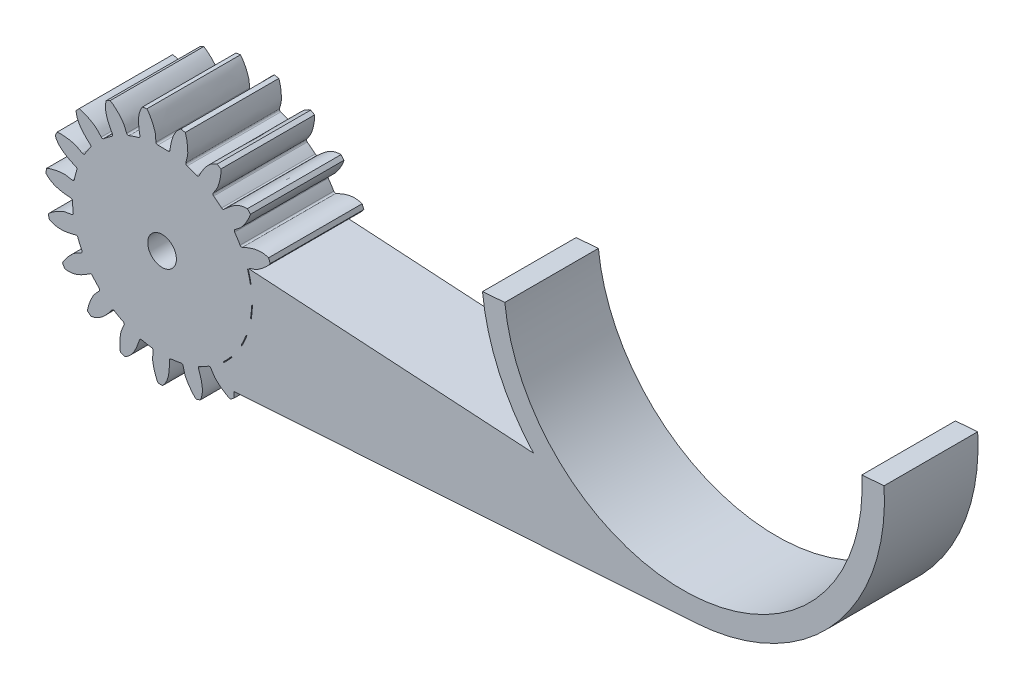
SolidWorks part; units mm, degrees
ref_plane "前视基准面" through (0, 0, 0) normal (0, 0, 1) x (1, 0, 0)
ref_plane "上视基准面" through (0, 0, 0) normal (0, 1, 0) x (1, 0, 0)
ref_plane "右视基准面" through (0, 0, 0) normal (1, 0, 0) x (0, 0, -1)
other "Configuration Table"
sketch "草图3" plane through (0, 0, 0) normal (0, 0, 1) x (1, 0, 0)
  circle A0 centre (0, 0) radius 13
  circle A1 centre (0, 0) radius 10
  dimension "D1" = 26
  dimension "D2" = 20
extrude "凸台-拉伸1" add sketch "草图3" along normal blind 4 contours A1 | A0 A1
sketch "草图6" plane through (0, 0, 4) normal (0, 0, 1) x (1, 0, 0)
  line L0 (0, 14.519) -> (0, -0.3622) construction
  line L5 (0, 0) -> (-1.6968, 12.8888) construction
  line L6 (-1.6968, 12.8888) -> (-1.8736, 14.2316)
  line L7 (-1.8736, 14.2316) -> (3.0009, 14.404)
  line L8 (3.0009, 14.404) -> (2.085, 12.8317)
  arc A0 (0.6559, 9.9785) -> (-0.4764, 9.9886) centre (0, 0) ccw
  circle A1 centre (0, 0) radius 13 construction
  arc A2 (0.6559, 9.9785) -> (0.8668, 10.1484) centre (0.669, 10.178) ccw
  arc A3 (-0.6854, 10.1744) -> (-0.4764, 9.9886) centre (-0.4859, 10.1884) ccw
  spline S0 degree 3 poles (-1.6968, 12.8888) (-1.3404, 12.4914) (-0.7219, 11.2236) (-0.7215, 10.6885) (-0.6854, 10.1744) knots 0 0 0 0 0.644244 0.940775 0.940775 0.940775 0.940775
  spline S1 degree 3 poles (2.085, 12.8317) (1.4718, 12.3854) (1.0735, 11.4242) (0.9081, 10.424) (0.8668, 10.1484) knots 0 0 0 0 0.67612 0.940775 0.940775 0.940775 0.940775
  dimension "D1" = 20
  dimension "D2" = 0.2
  dimension "D3" = 7.5
extrude "切除-拉伸2" cut sketch "草图6" against normal through all both
pattern_circular "阵列(圆周)4" count 19 every 18.947 about axis through (0, 0, 4) along (0, 0, 1) of "切除-拉伸2"
sketch "草图7" plane through (0, 0, 4) normal (0, 0, 1) x (1, 0, 0)
  circle A0 centre (0, 0) radius 12.5
  dimension "D1" = 25
ref_plane "基准面3" through (0, 0, 2) normal (0, 0, 1) x (1, 0, 0)
sketch "草图8" plane through (0, 0, 0) normal (0, 0, -1) x (-1, 0, 0)
  circle A5 centre (0, 0) radius 4.05
  dimension "D1" = 8.1
extrude "切除-拉伸4" cut sketch "草图8" against normal through all both
sketch "草图9" plane through (0, 0, 4) normal (0, 0, 1) x (1, 0, 0)
  line L8 (-1.8658, 22.9242) -> (0, 0) construction
  line L9 (41.4695, 1.1745) -> (9.5915, 3.1189)
  line L13 (0.8182, -10.0526) -> (59.6313, -6.1804)
  line L15 (-0.9329, 11.4621) -> (100.4696, 19.7151) construction
  line L16 (100.1482, 19.1873) -> (20.1614, 12.6773) construction
  line L17 (80.614, 17.5974) -> (78.1215, 17.3946)
  line L18 (0, 0) -> (20.4337, 1.6631) construction
  line L23 (0, 0) -> (1.9441, -23.887) construction
  line L26 (38.2658, 14.1508) -> (35.7734, 13.9479)
  arc A20 (0.8182, -10.0526) -> (9.5915, 3.1189) centre (0, 0) ccw
  arc A21 (38.2658, 14.1508) -> (78.1215, 17.3946) centre (58.1531, 16.271) ccw
  arc A22 (59.6313, -6.1804) -> (80.614, 17.5974) centre (58.1531, 16.271) ccw
  arc A23 (35.7734, 13.9479) -> (41.4695, 1.1745) centre (58.1531, 16.271) ccw
  dimension "D1" = 40
  dimension "D3" = 45
  dimension "D2" = 0.5
sketch "草图10" plane through (0, 0, 0) normal (0, 0, -1) x (-1, 0, 0)
  circle A0 centre (0, 0) radius 4.5
  dimension "D1" = 9
extrude "切除-拉伸5" cut sketch "草图10" against normal blind 0.6
sketch "草图11" plane through (0, 0, 4) normal (0, 0, 1) x (1, 0, 0)
  circle A0 centre (0, 0) radius 4.5
  dimension "D1" = 9
extrude "切除-拉伸6" cut sketch "草图11" against normal blind 0.6
sketch "草图15" plane through (0, 0, 4) normal (0, 0, 1) x (1, 0, 0)
  arc A62 (10.6318, -7.4809) -> (10.9134, -7.0638) centre (0, 0) ccw
  arc A64 (9.6948, 3.1621) -> (9.566, 2.9139) centre (9.7574, 2.9722) ccw
  arc A65 (12.0778, 4.8089) -> (11.8827, 5.2728) centre (0, 0) ccw
  arc A66 (8.7124, 4.9086) -> (8.97, 4.825) centre (8.8866, 5.0068) ccw
  arc A67 (8.7124, 4.9086) -> (8.1016, 5.8621) centre (0, 0) ccw
  arc A68 (8.1428, 6.1387) -> (8.1016, 5.8621) centre (8.2636, 5.9793) ccw
  arc A69 (9.862, 8.47) -> (9.5268, 8.8454) centre (0, 0) ccw
  arc A70 (6.6465, 7.4716) -> (6.9173, 7.4761) centre (6.7794, 7.621) ccw
  arc A71 (6.6465, 7.4716) -> (5.7592, 8.1751) centre (0, 0) ccw
  arc A72 (5.7084, 8.4501) -> (5.7592, 8.1751) centre (5.8744, 8.3386) ccw
  arc A73 (6.5774, 11.2133) -> (6.1385, 11.4595) centre (0, 0) ccw
  arc A74 (3.8603, 9.2248) -> (4.115, 9.3171) centre (3.9375, 9.4093) ccw
  arc A75 (3.8603, 9.2248) -> (2.7927, 9.6021) centre (0, 0) ccw
  arc A76 (2.6553, 9.8457) -> (2.7927, 9.6021) centre (2.8486, 9.7942) ccw
  arc A77 (2.5801, 12.7414) -> (2.085, 12.8317) centre (0, 0) ccw
  arc A78 (0.6559, 9.9785) -> (0.8668, 10.1484) centre (0.669, 10.178) ccw
  arc A79 (0.6559, 9.9785) -> (-0.4764, 9.9886) centre (0, 0) ccw
  arc A80 (-0.6854, 10.1744) -> (-0.4764, 9.9886) centre (-0.4859, 10.1884) ccw
  arc A81 (-1.6968, 12.8888) -> (-2.1944, 12.8134) centre (0, 0) ccw
  arc A82 (-2.6197, 9.6508) -> (-2.4754, 9.88) centre (-2.6721, 9.8438) ccw
  arc A83 (-2.6197, 9.6508) -> (-3.6939, 9.2927) centre (0, 0) ccw
  arc A84 (-3.9519, 9.4006) -> (-3.6939, 9.2927) centre (-3.7678, 9.4786) ccw
  arc A85 (-5.7899, 11.6395) -> (-6.236, 11.4067) centre (0, 0) ccw
  arc A86 (-5.6113, 8.2773) -> (-5.5493, 8.5409) centre (-5.7236, 8.4428) ccw
  arc A87 (-5.6113, 8.2773) -> (-6.5111, 7.5898) centre (0, 0) ccw
  arc A88 (-6.7902, 7.608) -> (-6.5111, 7.5898) centre (-6.6413, 7.7416) ccw
  arc A89 (-9.2555, 9.1288) -> (-9.6019, 8.7638) centre (0, 0) ccw
  arc A90 (-7.9949, 6.0068) -> (-8.0218, 6.2763) centre (-8.1548, 6.1269) ccw
  arc A91 (-7.9949, 6.0068) -> (-8.6227, 5.0644) centre (0, 0) ccw
  arc A92 (-8.8926, 4.9911) -> (-8.6227, 5.0644) centre (-8.7952, 5.1657) ccw
  arc A93 (-11.7181, 5.629) -> (-11.9272, 5.1712) centre (0, 0) ccw
  arc A94 (-9.5121, 3.0854) -> (-9.6251, 3.3315) centre (-9.7024, 3.1471) ccw
  arc A95 (-9.5121, 3.0854) -> (-9.7999, 1.9902) centre (0, 0) ccw
  arc A96 (-10.0314, 1.8332) -> (-9.7999, 1.9902) centre (-9.9959, 2.03) ccw
  arc A97 (-12.9109, 1.5191) -> (-12.9601, 1.0182) centre (0, 0) ccw
  arc A98 (-9.9985, -0.1704) -> (-10.1853, 0.0258) centre (-10.1985, -0.1738) ccw
  arc A99 (-9.9985, -0.1704) -> (-9.9152, -1.2996) centre (0, 0) ccw
  arc A100 (-10.0831, -1.5233) -> (-9.9152, -1.2996) centre (-10.1135, -1.3256) ccw
  arc A101 (-12.7046, -2.7554) -> (-12.5885, -3.2451) centre (0, 0) ccw
  arc A102 (-9.4015, -3.4077) -> (-9.6418, -3.2828) centre (-9.5895, -3.4758) ccw
  arc A103 (-9.4015, -3.4077) -> (-8.956, -4.4487) centre (0, 0) ccw
  arc A104 (-9.0421, -4.7147) -> (-8.956, -4.4487) centre (-9.1351, -4.5376) ccw
  arc A105 (-11.1216, -6.7313) -> (-10.8527, -7.1567) centre (0, 0) ccw
  arc A106 (-7.7856, -6.2757) -> (-8.0535, -6.2356) centre (-7.9413, -6.4012) ccw
  arc A107 (-7.7856, -6.2757) -> (-7.0262, -7.1156) centre (0, 0) ccw
  arc A108 (-7.0213, -7.3953) -> (-7.0262, -7.1156) centre (-7.1667, -7.2579) ccw
  arc A109 (-8.3333, -9.9777) -> (-7.9409, -10.2928) centre (0, 0) ccw
  arc A110 (-5.326, -8.4636) -> (-5.5924, -8.5127) centre (-5.4326, -8.6329) ccw
  arc A111 (-5.326, -8.4636) -> (-4.3351, -9.0115) centre (0, 0) ccw
  arc A112 (-4.2397, -9.2744) -> (-4.3351, -9.0115) centre (-4.4218, -9.1917) ccw
  arc A113 (-4.6421, -12.143) -> (-4.1686, -12.3135) centre (0, 0) ccw
  arc A114 (-2.2893, -9.7344) -> (-2.5253, -9.8673) centre (-2.3351, -9.9291) ccw
  arc A115 (-2.2893, -9.7344) -> (-1.1742, -9.9308) centre (0, 0) ccw
  arc A116 (-0.9986, -10.1485) -> (-1.1742, -9.9308) centre (-1.1976, -10.1294) ccw
  arc A117 (-0.4477, -12.9923) -> (0.0555, -12.9999) centre (0, 0) ccw
  arc A118 (0.9955, -9.9503) -> (0.8154, -10.1526) centre (1.0154, -10.1493) ccw
  arc A119 (3.7951, -12.4337) -> (4.2735, -12.2775) centre (0, 0) ccw
  arc A120 (7.6267, -10.5277) -> (8.0285, -10.2247) centre (0, 0) ccw
  arc A121 (10.6318, -7.4809) -> (10.9134, -7.0638) centre (0, 0) ccw
  arc A122 (8.8746, -4.6089) -> (8.9454, -4.8703) centre (9.052, -4.7011) ccw
  arc A123 (8.8746, -4.6089) -> (8.9454, -4.8703) centre (9.052, -4.7011) ccw
  arc A126 (9.6948, 3.1621) -> (9.566, 2.9139) centre (9.7574, 2.9722) ccw
  arc A127 (12.0778, 4.8089) -> (11.8827, 5.2728) centre (0, 0) ccw
  arc A128 (8.7124, 4.9086) -> (8.97, 4.825) centre (8.8866, 5.0068) ccw
  arc A129 (8.7124, 4.9086) -> (8.1016, 5.8621) centre (0, 0) ccw
  arc A130 (8.1428, 6.1387) -> (8.1016, 5.8621) centre (8.2636, 5.9793) ccw
  arc A131 (9.862, 8.47) -> (9.5268, 8.8454) centre (0, 0) ccw
  arc A132 (6.6465, 7.4716) -> (6.9173, 7.4761) centre (6.7794, 7.621) ccw
  arc A133 (6.6465, 7.4716) -> (5.7592, 8.1751) centre (0, 0) ccw
  arc A134 (5.7084, 8.4501) -> (5.7592, 8.1751) centre (5.8744, 8.3386) ccw
  arc A135 (6.5774, 11.2133) -> (6.1385, 11.4595) centre (0, 0) ccw
  arc A136 (3.8603, 9.2248) -> (4.115, 9.3171) centre (3.9375, 9.4093) ccw
  arc A137 (3.8603, 9.2248) -> (2.7927, 9.6021) centre (0, 0) ccw
  arc A138 (2.6553, 9.8457) -> (2.7927, 9.6021) centre (2.8486, 9.7942) ccw
  arc A139 (2.5801, 12.7414) -> (2.085, 12.8317) centre (0, 0) ccw
  arc A140 (0.6559, 9.9785) -> (0.8668, 10.1484) centre (0.669, 10.178) ccw
  arc A141 (0.6559, 9.9785) -> (-0.4764, 9.9886) centre (0, 0) ccw
  arc A142 (-0.6854, 10.1744) -> (-0.4764, 9.9886) centre (-0.4859, 10.1884) ccw
  arc A143 (-1.6968, 12.8888) -> (-2.1944, 12.8134) centre (0, 0) ccw
  arc A144 (-2.6197, 9.6508) -> (-2.4754, 9.88) centre (-2.6721, 9.8438) ccw
  arc A145 (-2.6197, 9.6508) -> (-3.6939, 9.2927) centre (0, 0) ccw
  arc A146 (-3.9519, 9.4006) -> (-3.6939, 9.2927) centre (-3.7678, 9.4786) ccw
  arc A147 (-5.7899, 11.6395) -> (-6.236, 11.4067) centre (0, 0) ccw
  arc A148 (-5.6113, 8.2773) -> (-5.5493, 8.5409) centre (-5.7236, 8.4428) ccw
  arc A149 (-5.6113, 8.2773) -> (-6.5111, 7.5898) centre (0, 0) ccw
  arc A150 (-6.7902, 7.608) -> (-6.5111, 7.5898) centre (-6.6413, 7.7416) ccw
  arc A151 (-9.2555, 9.1288) -> (-9.6019, 8.7638) centre (0, 0) ccw
  arc A152 (-7.9949, 6.0068) -> (-8.0218, 6.2763) centre (-8.1548, 6.1269) ccw
  arc A153 (-7.9949, 6.0068) -> (-8.6227, 5.0644) centre (0, 0) ccw
  arc A154 (-8.8926, 4.9911) -> (-8.6227, 5.0644) centre (-8.7952, 5.1657) ccw
  arc A155 (-11.7181, 5.629) -> (-11.9272, 5.1712) centre (0, 0) ccw
  arc A156 (-9.5121, 3.0854) -> (-9.6251, 3.3315) centre (-9.7024, 3.1471) ccw
  arc A157 (-9.5121, 3.0854) -> (-9.7999, 1.9902) centre (0, 0) ccw
  arc A158 (-10.0314, 1.8332) -> (-9.7999, 1.9902) centre (-9.9959, 2.03) ccw
  arc A159 (-12.9109, 1.5191) -> (-12.9601, 1.0182) centre (0, 0) ccw
  arc A160 (-9.9985, -0.1704) -> (-10.1853, 0.0258) centre (-10.1985, -0.1738) ccw
  arc A161 (-9.9985, -0.1704) -> (-9.9152, -1.2996) centre (0, 0) ccw
  arc A162 (-10.0831, -1.5233) -> (-9.9152, -1.2996) centre (-10.1135, -1.3256) ccw
  arc A163 (-12.7046, -2.7554) -> (-12.5885, -3.2451) centre (0, 0) ccw
  arc A164 (-9.4015, -3.4077) -> (-9.6418, -3.2828) centre (-9.5895, -3.4758) ccw
  arc A165 (-9.4015, -3.4077) -> (-8.956, -4.4487) centre (0, 0) ccw
  arc A166 (-9.0421, -4.7147) -> (-8.956, -4.4487) centre (-9.1351, -4.5376) ccw
  arc A167 (-11.1216, -6.7313) -> (-10.8527, -7.1567) centre (0, 0) ccw
  arc A168 (-7.7856, -6.2757) -> (-8.0535, -6.2356) centre (-7.9413, -6.4012) ccw
  arc A169 (-7.7856, -6.2757) -> (-7.0262, -7.1156) centre (0, 0) ccw
  arc A170 (-7.0213, -7.3953) -> (-7.0262, -7.1156) centre (-7.1667, -7.2579) ccw
  arc A171 (-8.3333, -9.9777) -> (-7.9409, -10.2928) centre (0, 0) ccw
  arc A172 (-5.326, -8.4636) -> (-5.5924, -8.5127) centre (-5.4326, -8.6329) ccw
  arc A173 (-5.326, -8.4636) -> (-4.3351, -9.0115) centre (0, 0) ccw
  arc A174 (-4.2397, -9.2744) -> (-4.3351, -9.0115) centre (-4.4218, -9.1917) ccw
  arc A175 (-4.6421, -12.143) -> (-4.1686, -12.3135) centre (0, 0) ccw
  arc A176 (-2.2893, -9.7344) -> (-2.5253, -9.8673) centre (-2.3351, -9.9291) ccw
  arc A177 (-2.2893, -9.7344) -> (-1.1742, -9.9308) centre (0, 0) ccw
  arc A178 (-0.9986, -10.1485) -> (-1.1742, -9.9308) centre (-1.1976, -10.1294) ccw
  arc A179 (-0.4477, -12.9923) -> (0.0555, -12.9999) centre (0, 0) ccw
  arc A180 (0.9955, -9.9503) -> (0.8154, -10.1526) centre (1.0154, -10.1493) ccw
  arc A181 (3.7951, -12.4337) -> (4.2735, -12.2775) centre (0, 0) ccw
  arc A182 (7.6267, -10.5277) -> (8.0285, -10.2247) centre (0, 0) ccw
  arc A199 (8.8746, -4.6089) -> (9.3387, -3.5761) centre (0, 0) ccw
  arc A200 (8.8746, -4.6089) -> (9.3387, -3.5761) centre (0, 0) ccw
  arc A201 (9.5928, -3.4593) -> (9.3387, -3.5761) centre (9.5255, -3.6476) ccw
  arc A202 (9.5928, -3.4593) -> (9.3387, -3.5761) centre (9.5255, -3.6476) ccw
  arc A203 (12.4848, -3.6234) -> (12.6157, -3.1375) centre (0, 0) ccw
  arc A204 (12.4848, -3.6234) -> (12.6157, -3.1375) centre (0, 0) ccw
  arc A205 (9.8902, -1.4776) -> (10.0421, -1.7019) centre (10.088, -1.5072) ccw
  arc A206 (9.8902, -1.4776) -> (10.0421, -1.7019) centre (10.088, -1.5072) ccw
  arc A207 (9.8902, -1.4776) -> (9.9939, -0.3501) centre (0, 0) ccw
  arc A208 (9.8902, -1.4776) -> (9.9939, -0.3501) centre (0, 0) ccw
  arc A209 (10.1963, -0.1571) -> (9.9939, -0.3501) centre (10.1937, -0.3571) ccw
  arc A210 (10.1963, -0.1571) -> (9.9939, -0.3501) centre (10.1937, -0.3571) ccw
  arc A211 (12.9849, 0.6267) -> (12.9509, 1.1288) centre (0, 0) ccw
  arc A212 (12.9849, 0.6267) -> (12.9509, 1.1288) centre (0, 0) ccw
  arc A213 (9.8341, 1.8138) -> (10.0506, 1.651) centre (10.0308, 1.85) ccw
  arc A214 (9.8341, 1.8138) -> (10.0506, 1.651) centre (10.0308, 1.85) ccw
  arc A215 (9.8341, 1.8138) -> (9.566, 2.9139) centre (0, 0) ccw
  arc A216 (9.8341, 1.8138) -> (9.566, 2.9139) centre (0, 0) ccw
  arc A217 (0.9955, -9.9503) -> (2.114, -9.774) centre (0, 0) ccw
  arc A218 (0.9955, -9.9503) -> (2.114, -9.774) centre (0, 0) ccw
  arc A219 (2.3508, -9.9228) -> (2.114, -9.774) centre (2.1563, -9.9695) ccw
  arc A220 (2.3508, -9.9228) -> (2.114, -9.774) centre (2.1563, -9.9695) ccw
  arc A221 (4.1724, -9.088) -> (4.0678, -9.3378) centre (4.2559, -9.2697) ccw
  arc A222 (4.1724, -9.088) -> (4.0678, -9.3378) centre (4.2559, -9.2697) ccw
  arc A223 (4.1724, -9.088) -> (5.1731, -8.558) centre (0, 0) ccw
  arc A224 (4.1724, -9.088) -> (5.1731, -8.558) centre (0, 0) ccw
  arc A225 (5.4453, -8.6219) -> (5.1731, -8.558) centre (5.2765, -8.7292) ccw
  arc A226 (5.4453, -8.6219) -> (5.1731, -8.558) centre (5.2765, -8.7292) ccw
  arc A227 (6.8972, -7.2408) -> (6.8794, -7.511) centre (7.0351, -7.3856) ccw
  arc A228 (6.8972, -7.2408) -> (6.8794, -7.511) centre (7.0351, -7.3856) ccw
  arc A229 (6.8972, -7.2408) -> (7.6715, -6.4146) centre (0, 0) ccw
  arc A230 (6.8972, -7.2408) -> (7.6715, -6.4146) centre (0, 0) ccw
  arc A231 (7.9498, -6.3867) -> (7.6715, -6.4146) centre (7.825, -6.5429) ccw
  arc A232 (7.9498, -6.3867) -> (7.6715, -6.4146) centre (7.825, -6.5429) ccw
  spline S31 degree 3 poles (-2677.4237, -1330.5887) (22.7629, 27.6924) (-22.3883, -45.1849) (88.5545, 99.6825) (-2408.7051, -1766.8032) knots -5.42301 -5.42301 -5.42301 -5.42301 0.296531 10.304732 10.304732 10.304732 10.304732 only from (9.6948, 3.1621) to (12.0778, 4.8089)
  spline S32 degree 3 poles (-588.9236, -2933.2866) (60.6828, -34.2879) (-15.1797, 58.9043) (3.9973, -65.0173) (76.3332, 3003.9302) knots -13.632919 -13.632919 -13.632919 -13.632919 0.67612 16.178523 16.178523 16.178523 16.178523 only from (11.8827, 5.2728) to (8.97, 4.825)
  spline S33 degree 3 poles (-2100.312, -2127.8518) (12.5379, 33.583) (-6.5038, -50.0061) (51.3895, 123.0351) (-1704.5147, -2453.1782) knots -5.42301 -5.42301 -5.42301 -5.42301 0.296531 10.304732 10.304732 10.304732 10.304732 only from (8.1428, 6.1387) to (9.862, 8.47)
  spline S34 degree 3 poles (395.4225, -2965.5762) (68.5281, -12.7264) (-33.4834, 50.7839) (24.8918, -60.1966) (-903.1772, 2865.9543) knots -13.632919 -13.632919 -13.632919 -13.632919 0.67612 16.178523 16.178523 16.178523 16.178523 only from (9.5268, 8.8454) to (6.9173, 7.4761)
  spline S35 degree 3 poles (-1295.599, -2694.5291) (0.9541, 35.8345) (10.0856, -49.4084) (8.6557, 133.0548) (-815.6138, -2873.7133) knots -5.42301 -5.42301 -5.42301 -5.42301 0.296531 10.304732 10.304732 10.304732 10.304732 only from (5.7084, 8.4501) to (6.5774, 11.2133)
  spline S36 degree 3 poles (1336.9185, -2676.4996) (68.9473, 10.2142) (-48.1587, 37.1602) (43.0889, -48.8526) (-1784.8144, 2417.4078) knots -13.632919 -13.632919 -13.632919 -13.632919 0.67612 16.178523 16.178523 16.178523 16.178523 only from (6.1385, 11.4595) to (4.115, 9.3171)
  spline S37 degree 3 poles (-350.4877, -2969.2124) (-10.733, 34.2027) (25.582, -43.4566) (-35.0162, 128.6561) (161.6716, -2982.8369) knots -5.42301 -5.42301 -5.42301 -5.42301 0.296531 10.304732 10.304732 10.304732 10.304732 only from (2.6553, 9.8457) to (2.5801, 12.7414)
  spline S38 degree 3 poles (2133.5385, -2097.3828) (61.895, 32.0479) (-57.6152, 19.5097) (56.6166, -32.2147) (-2473.0393, 1706.8977) knots -13.632919 -13.632919 -13.632919 -13.632919 0.67612 16.178523 16.178523 16.178523 16.178523 only from (2.085, 12.8317) to (0.8668, 10.1484)
  spline S39 degree 3 poles (632.6044, -2922.1354) (-21.257, 28.8645) (38.3062, -32.7955) (-74.8934, 110.3154) (1121.4373, -2768.7239) knots -5.42301 -5.42301 -5.42301 -5.42301 0.296531 10.304732 10.304732 10.304732 10.304732 only from (-0.6854, 10.1744) to (-1.6968, 12.8888)
  spline S40 degree 3 poles (2698.9566, -1290.982) (48.1355, 50.4087) (-60.8283, -0.255) (64.0091, -12.0858) (-2893.272, 811.4187) knots -13.632919 -13.632919 -13.632919 -13.632919 0.67612 16.178523 16.178523 16.178523 16.178523 only from (-2.1944, 12.8134) to (-2.4754, 9.88)
  spline S41 degree 3 poles (1547.144, -2558.3998) (-29.4775, 20.3984) (46.8794, -18.5805) (-106.6549, 80.0203) (1959.6779, -2254.5767) knots -5.42301 -5.42301 -5.42301 -5.42301 0.296531 10.304732 10.304732 10.304732 10.304732 only from (-3.9519, 9.4006) to (-5.7899, 11.6395)
  spline S42 degree 3 poles (2971.9008, -344.6832) (29.1597, 63.307) (-57.4496, -19.9921) (64.4651, 9.3528) (-2999.9738, -171.9901) knots -13.632919 -13.632919 -13.632919 -13.632919 0.67612 16.178523 16.178523 16.178523 16.178523 only from (-6.236, 11.4067) to (-5.5493, 8.5409)
  spline S43 degree 3 poles (2294.0265, -1917.4218) (-34.5037, 9.7218) (50.3724, -2.3521) (-126.8586, 41.0538) (2585.557, -1496.1111) knots -5.42301 -5.42301 -5.42301 -5.42301 0.296531 10.304732 10.304732 10.304732 10.304732 only from (-6.7902, 7.608) to (-9.2555, 9.1288)
  spline S44 degree 3 poles (2922.7935, 638.9673) (7.024, 69.345) (-47.8454, -37.5628) (57.9354, 29.7778) (-2781.5818, -1136.7611) knots -13.632919 -13.632919 -13.632919 -13.632919 0.67612 16.178523 16.178523 16.178523 16.178523 only from (-9.6019, 8.7638) to (-8.0218, 6.2763)
  spline S45 degree 3 poles (2792.3156, -1068.6614) (-35.7909, -2.0083) (48.4068, 14.1313) (-133.3152, -2.3615) (2931.2509, -575.5187) knots -5.42301 -5.42301 -5.42301 -5.42301 0.296531 10.304732 10.304732 10.304732 10.304732 only from (-8.8926, 4.9911) to (-11.7181, 5.629)
  spline S46 degree 3 poles (2556.9562, 1553.3758) (-15.8729, 67.8684) (-33.0564, -51.0629) (45.1275, 46.976) (-2261.7623, -1978.3464) knots -13.632919 -13.632919 -13.632919 -13.632919 0.67612 16.178523 16.178523 16.178523 16.178523 only from (-11.9272, 5.1712) to (-9.6251, 3.3315)
  spline S47 degree 3 poles (2988.0141, -104.095) (-33.1995, -13.5208) (41.1956, 29.0833) (-125.325, -45.5209) (2959.2983, 407.4401) knots -5.42301 -5.42301 -5.42301 -5.42301 0.296531 10.304732 10.304732 10.304732 10.304732 only from (-10.0314, 1.8332) to (-12.9109, 1.5191)
  spline S48 degree 3 poles (1914.0329, 2299.4519) (-37.0497, 59.0371) (-14.6852, -59.0295) (27.4293, 59.0835) (-1496.8458, -2605.5471) knots -13.632919 -13.632919 -13.632919 -13.632919 0.67612 16.178523 16.178523 16.178523 16.178523 only from (-12.9601, 1.0182) to (-10.1853, 0.0258)
  spline S49 degree 3 poles (2859.9148, 871.7518) (-27.0105, -23.568) (29.5202, 40.8836) (-103.754, -83.7474) (2666.6597, 1346.2465) knots -5.42301 -5.42301 -5.42301 -5.42301 0.296531 10.304732 10.304732 10.304732 10.304732 only from (-10.0831, -1.5233) to (-12.7046, -2.7554)
  spline S50 degree 3 poles (1063.6945, 2796.3467) (-54.2115, 43.8083) (5.2773, -60.5994) (6.7587, 64.7885) (-569.7228, -2950.3964) knots -13.632919 -13.632919 -13.632919 -13.632919 0.67612 16.178523 16.178523 16.178523 16.178523 only from (-12.5885, -3.2451) to (-9.6418, -3.2828)
  spline S51 degree 3 poles (2421.8994, 1753.1307) (-17.8945, -31.0614) (14.6458, 48.2536) (-70.9395, -112.8986) (2085.0472, 2139.1661) knots -5.42301 -5.42301 -5.42301 -5.42301 0.296531 10.304732 10.304732 10.304732 10.304732 only from (-9.0421, -4.7147) to (-11.1216, -6.7313)
  spline S52 degree 3 poles (98.0883, 2990.214) (-65.4988, 23.8322) (24.668, -55.6025) (-14.6443, 63.4726) (419.1385, -2975.5245) knots -13.632919 -13.632919 -13.632919 -13.632919 0.67612 16.178523 16.178523 16.178523 16.178523 only from (-10.8527, -7.1567) to (-8.0535, -6.2356)
  spline S53 degree 3 poles (1721.4336, 2444.5307) (-6.8393, -35.1887) (-1.8157, 50.3946) (-30.4377, -129.8155) (1277.4875, 2700.2739) knots -5.42301 -5.42301 -5.42301 -5.42301 0.296531 10.304732 10.304732 10.304732 10.304732 only from (-7.0213, -7.3953) to (-8.3333, -9.9777)
  spline S54 degree 3 poles (-878.1473, 2860.0452) (-69.6882, 1.2735) (41.3855, -44.5801) (-34.4604, 55.2785) (1362.5797, -2678.2083) knots -13.632919 -13.632919 -13.632919 -13.632919 0.67612 16.178523 16.178523 16.178523 16.178523 only from (-7.9409, -10.2928) to (-5.5924, -8.5127)
  spline S55 degree 3 poles (834.4238, 2871.0278) (4.957, -35.5028) (-18.0804, 47.0745) (13.3625, -132.6648) (331.4922, 2968.7652) knots -5.42301 -5.42301 -5.42301 -5.42301 0.296531 10.304732 10.304732 10.304732 10.304732 only from (-4.2397, -9.2744) to (-4.6421, -12.143)
  spline S56 degree 3 poles (-1759.222, 2419.9461) (-66.3258, -21.4232) (53.6182, -28.7268) (-50.5421, 41.0941) (2158.3642, -2090.6667) knots -13.632919 -13.632919 -13.632919 -13.632919 0.67612 16.178523 16.178523 16.178523 16.178523 only from (-4.1686, -12.3135) to (-2.5253, -9.8673)
  spline S57 degree 3 poles (-143.0088, 2986.4046) (16.2162, -31.9696) (-32.3858, 38.6532) (55.7147, -121.1379) (-650.4254, 2915.5446) knots -5.42301 -5.42301 -5.42301 -5.42301 0.296531 10.304732 10.304732 10.304732 10.304732 only from (-0.9986, -10.1485) to (-0.4477, -12.9923)
  spline S58 degree 3 poles (-2449.6577, 1717.6083) (-55.776, -41.7984) (60.0406, -9.7604) (-61.1468, 22.4565) (2720.2564, -1276.5689) knots -13.632919 -13.632919 -13.632919 -13.632919 0.67612 16.178523 16.178523 16.178523 16.178523 only from (0.0555, -12.9999) to (0.8154, -10.1526)
  spline S59 degree 3 poles (-1104.9442, 2778.158) (25.7181, -24.972) (-43.1818, 26.0432) (92.0293, -96.4838) (-1561.8594, 2546.3796) knots -5.42301 -5.42301 -5.42301 -5.42301 0.296531 10.304732 10.304732 10.304732 10.304732 only from (2.3508, -9.9228) to (3.7951, -12.4337)
  spline S60 degree 3 poles (-2874.635, 829.141) (-39.182, -57.6441) (59.9567, 10.2636) (-65.1253, 1.3854) (2987.3667, -324.1351) knots -13.632919 -13.632919 -13.632919 -13.632919 0.67612 16.178523 16.178523 16.178523 16.178523 only from (4.2735, -12.2775) to (4.0678, -9.3378)
  spline S61 degree 3 poles (-1947.1417, 2268.855) (32.433, -15.2683) (-49.2983, 10.611) (118.3711, -61.3742) (-2304.0416, 1901.2748) knots -5.42301 -5.42301 -5.42301 -5.42301 0.296531 10.304732 10.304732 10.304732 10.304732 only from (5.4453, -8.6219) to (7.6267, -10.5277)
  spline S62 degree 3 poles (9.6948, 3.1621) (10.1843, 3.3233) (10.7029, 3.455) (11.7801, 4.3658) (12.0778, 4.8089) knots 0 0 0 0 0.296531 0.940775 0.940775 0.940775 0.940775
  spline S63 degree 3 poles (11.8827, 5.2728) (11.1736, 5.5421) (10.1511, 5.3497) (9.2233, 4.9412) (8.97, 4.825) knots 0 0 0 0 0.67612 0.940775 0.940775 0.940775 0.940775
  spline S64 degree 3 poles (8.1428, 6.1387) (8.5534, 6.45) (9.0012, 6.743) (9.7242, 7.9542) (9.862, 8.47) knots 0 0 0 0 0.296531 0.940775 0.940775 0.940775 0.940775
  spline S65 degree 3 poles (9.5268, 8.8454) (8.7687, 8.8699) (7.8641, 8.3559) (7.1192, 7.6683) (6.9173, 7.4761) knots 0 0 0 0 0.67612 0.940775 0.940775 0.940775 0.940775
  spline S66 degree 3 poles (5.7084, 8.4501) (5.9956, 8.8778) (6.324, 9.3003) (6.6146, 10.6807) (6.5774, 11.2133) knots 0 0 0 0 0.296531 0.940775 0.940775 0.940775 0.940775
  spline S67 degree 3 poles (6.1385, 11.4595) (5.4135, 11.2365) (4.7248, 10.4567) (4.2436, 9.5644) (4.115, 9.3171) knots 0 0 0 0 0.67612 0.940775 0.940775 0.940775 0.940775
  spline S68 degree 3 poles (2.6553, 9.8457) (2.7881, 10.3436) (2.9615, 10.8498) (2.7882, 12.2498) (2.5801, 12.7414) knots 0 0 0 0 0.296531 0.940775 0.940775 0.940775 0.940775
  spline S69 degree 3 poles (2.085, 12.8317) (1.4718, 12.3854) (1.0735, 11.4242) (0.9081, 10.424) (0.8668, 10.1484) knots 0 0 0 0 0.67612 0.940775 0.940775 0.940775 0.940775
  spline S70 degree 3 poles (-0.6854, 10.1744) (-0.7215, 10.6885) (-0.7219, 11.2236) (-1.3404, 12.4914) (-1.6968, 12.8888) knots 0 0 0 0 0.296531 0.940775 0.940775 0.940775 0.940775
  spline S71 degree 3 poles (-2.1944, 12.8134) (-2.6295, 12.1922) (-2.6941, 11.1538) (-2.5258, 10.1541) (-2.4754, 9.88) knots 0 0 0 0 0.67612 0.940775 0.940775 0.940775 0.940775
  spline S72 degree 3 poles (-3.9519, 9.4006) (-4.1529, 9.8751) (-4.327, 10.3811) (-5.3237, 11.3793) (-5.7899, 11.6395) knots 0 0 0 0 0.296531 0.940775 0.940775 0.940775 0.940775
  spline S73 degree 3 poles (-6.236, 11.4067) (-6.4459, 10.6778) (-6.1697, 9.6747) (-5.6859, 8.7838) (-5.5493, 8.5409) knots 0 0 0 0 0.67612 0.940775 0.940775 0.940775 0.940775
  spline S74 degree 3 poles (-6.7902, 7.608) (-7.1343, 7.9916) (-7.4633, 8.4136) (-8.7301, 9.0342) (-9.2555, 9.1288) knots 0 0 0 0 0.296531 0.940775 0.940775 0.940775 0.940775
  spline S75 degree 3 poles (-9.6019, 8.7638) (-9.5637, 8.0063) (-8.9768, 7.1472) (-8.23, 6.4616) (-8.0218, 6.2763) knots 0 0 0 0 0.67612 0.940775 0.940775 0.940775 0.940775
  spline S76 degree 3 poles (-8.8926, 4.9911) (-9.3426, 5.242) (-9.7908, 5.5344) (-11.1905, 5.71) (-11.7181, 5.629) knots 0 0 0 0 0.296531 0.940775 0.940775 0.940775 0.940775
  spline S77 degree 3 poles (-11.9272, 5.1712) (-11.6451, 4.4672) (-10.8111, 3.8452) (-9.8821, 3.4392) (-9.6251, 3.3315) knots 0 0 0 0 0.67612 0.940775 0.940775 0.940775 0.940775
  spline S78 degree 3 poles (-10.0314, 1.8332) (-10.5385, 1.9245) (-11.0573, 2.0555) (-12.4382, 1.7671) (-12.9109, 1.5191) knots 0 0 0 0 0.296531 0.940775 0.940775 0.940775 0.940775
  spline S79 degree 3 poles (-12.9601, 1.0182) (-12.4646, 0.4439) (-11.4739, 0.1265) (-10.4634, 0.0442) (-10.1853, 0.0258) knots 0 0 0 0 0.67612 0.940775 0.940775 0.940775 0.940775
  spline S80 degree 3 poles (-10.0831, -1.5233) (-10.5924, -1.6017) (-11.1256, -1.6462) (-12.338, -2.3673) (-12.7046, -2.7554) knots 0 0 0 0 0.296531 0.940775 0.940775 0.940775 0.940775
  spline S81 degree 3 poles (-12.5885, -3.2451) (-11.9334, -3.6274) (-10.8932, -3.6059) (-9.9108, -3.3557) (-9.6418, -3.2828) knots 0 0 0 0 0.67612 0.940775 0.940775 0.940775 0.940775
  spline S82 degree 3 poles (-9.0421, -4.7147) (-9.4984, -4.9542) (-9.9883, -5.1695) (-10.9008, -6.2452) (-11.1216, -6.7313) knots 0 0 0 0 0.296531 0.940775 0.940775 0.940775 0.940775
  spline S83 degree 3 poles (-10.8527, -7.1567) (-10.109, -7.3056) (-9.1322, -6.9476) (-8.2842, -6.3919) (-8.0535, -6.2356) knots 0 0 0 0 0.67612 0.940775 0.940775 0.940775 0.940775
  spline S84 degree 3 poles (-7.0213, -7.3953) (-7.3751, -7.7699) (-7.7686, -8.1326) (-8.2824, -9.4463) (-8.3333, -9.9777) knots 0 0 0 0 0.296531 0.940775 0.940775 0.940775 0.940775
  spline S85 degree 3 poles (-7.9409, -10.2928) (-7.1892, -10.1922) (-6.3815, -9.5364) (-5.7599, -8.7354) (-5.5924, -8.5127) knots 0 0 0 0 0.67612 0.940775 0.940775 0.940775 0.940775
  spline S86 degree 3 poles (-4.2397, -9.2744) (-4.4526, -9.7436) (-4.707, -10.2144) (-4.7664, -11.6238) (-4.6421, -12.143) knots 0 0 0 0 0.296531 0.940775 0.940775 0.940775 0.940775
  spline S87 degree 3 poles (-4.1686, -12.3135) (-3.4902, -11.9742) (-2.9393, -11.0917) (-2.6114, -10.1324) (-2.5253, -9.8673) knots 0 0 0 0 0.67612 0.940775 0.940775 0.940775 0.940775
  spline S88 degree 3 poles (-0.9986, -10.1485) (-1.0476, -10.6614) (-1.1353, -11.1893) (-0.7339, -12.5416) (-0.4477, -12.9923) knots 0 0 0 0 0.296531 0.940775 0.940775 0.940775 0.940775
  spline S89 degree 3 poles (0.0555, -12.9999) (0.5869, -12.4587) (0.8215, -11.4451) (0.82, -10.4313) (0.8154, -10.1526) knots 0 0 0 0 0.67612 0.940775 0.940775 0.940775 0.940775
  spline S90 degree 3 poles (2.3508, -9.9228) (2.4709, -10.4239) (2.5593, -10.9517) (3.3781, -12.1004) (3.7951, -12.4337) knots 0 0 0 0 0.296531 0.940775 0.940775 0.940775 0.940775
  spline S91 degree 3 poles (4.2735, -12.2775) (4.6004, -11.5931) (4.4932, -10.5582) (4.1626, -9.5998) (4.0678, -9.3378) knots 0 0 0 0 0.67612 0.940775 0.940775 0.940775 0.940775
  spline S92 degree 3 poles (5.4453, -8.6219) (5.7217, -9.0568) (5.9767, -9.5273) (7.1241, -10.3479) (7.6267, -10.5277) knots 0 0 0 0 0.296531 0.940775 0.940775 0.940775 0.940775
  spline S100 degree 3 poles (-2988.101, -149.1766) (-18.342, -67.2431) (53.3755, 29.1753) (-62.0465, -19.8358) (2930.7494, 663.4238) knots -13.632919 -13.632919 -13.632919 -13.632919 0.67612 16.178523 16.178523 16.178523 16.178523 only from (8.0285, -10.2247) to (6.8794, -7.511)
  spline S101 degree 3 poles (8.0285, -10.2247) (8.1155, -9.4712) (7.678, -8.5272) (7.0542, -7.7281) (6.8794, -7.511) knots 0 0 0 0 0.67612 0.940775 0.940775 0.940775 0.940775
  spline S102 degree 3 poles (-2578.3362, 1513.6863) (35.6333, -3.9101) (-50.0725, -5.971) (131.8856, -19.6137) (-2796.5452, 1050.1374) knots -5.42301 -5.42301 -5.42301 -5.42301 0.296531 10.304732 10.304732 10.304732 10.304732 only from (7.9498, -6.3867) to (10.6318, -7.4809)
  spline S103 degree 3 poles (7.9498, -6.3867) (8.3524, -6.7083) (8.7464, -7.0704) (10.098, -7.474) (10.6318, -7.4809) knots 0 0 0 0 0.296531 0.940775 0.940775 0.940775 0.940775
  spline S104 degree 3 poles (-2777.7599, -1111.3286) (4.4856, -69.5553) (41.0102, 44.9255) (-52.244, -38.9075) (2556.5399, 1579.0904) knots -13.632919 -13.632919 -13.632919 -13.632919 0.67612 16.178523 16.178523 16.178523 16.178523 only from (10.9134, -7.0638) to (8.9454, -4.8703)
  spline S105 degree 3 poles (10.9134, -7.0638) (10.751, -6.323) (10.0308, -5.5722) (9.1813, -5.0189) (8.9454, -4.8703) knots 0 0 0 0 0.67612 0.940775 0.940775 0.940775 0.940775
  spline S106 degree 3 poles (-2930.128, 594.4862) (34.9722, 7.8719) (-45.4207, -21.906) (131.1082, 24.2722) (-2985.9997, 85.2013) knots -5.42301 -5.42301 -5.42301 -5.42301 0.296531 10.304732 10.304732 10.304732 10.304732 only from (9.5928, -3.4593) to (12.4848, -3.6234)
  spline S107 degree 3 poles (9.5928, -3.4593) (10.078, -3.6328) (10.5682, -3.8474) (11.9777, -3.7902) (12.4848, -3.6234) knots 0 0 0 0 0.296531 0.940775 0.940775 0.940775 0.940775
  spline S108 degree 3 poles (-2266.4054, -1953.0509) (26.8272, -64.3301) (24.2009, 55.8073) (-36.78, -53.763) (1905.2897, 2323.6381) knots -13.632919 -13.632919 -13.632919 -13.632919 0.67612 16.178523 16.178523 16.178523 16.178523 only from (12.6157, -3.1375) to (10.0421, -1.7019)
  spline S109 degree 3 poles (12.6157, -3.1375) (12.2216, -2.4895) (11.2966, -2.0133) (10.3134, -1.7658) (10.0421, -1.7019) knots 0 0 0 0 0.67612 0.940775 0.940775 0.940775 0.940775
  spline S110 degree 3 poles (-2964.3949, -389.1357) (30.5213, 18.8008) (-35.8468, -35.4672) (116.1233, 65.5279) (-2851.8749, -888.9677) knots -5.42301 -5.42301 -5.42301 -5.42301 0.296531 10.304732 10.304732 10.304732 10.304732 only from (10.1963, -0.1571) to (12.9849, 0.6267)
  spline S111 degree 3 poles (10.1963, -0.1571) (10.7115, -0.1636) (11.2449, -0.2074) (12.5594, 0.3043) (12.9849, 0.6267) knots 0 0 0 0 0.296531 0.940775 0.940775 0.940775 0.940775
  spline S112 degree 3 poles (-1509.4507, -2583.1298) (46.2616, -52.1338) (4.769, 60.6416) (-17.3303, -62.7924) (1047.5718, 2816.3836) knots -13.632919 -13.632919 -13.632919 -13.632919 0.67612 16.178523 16.178523 16.178523 16.178523 only from (12.9509, 1.1288) to (10.0506, 1.651)
  spline S113 degree 3 poles (12.9509, 1.1288) (12.3677, 1.6137) (11.3382, 1.7638) (10.328, 1.6786) (10.0506, 1.651) knots 0 0 0 0 0.67612 0.940775 0.940775 0.940775 0.940775
  dimension "D1" = 0
extrude "凸台-拉伸6" add sketch "草图15" along normal blind 6.45
sketch "草图16" plane through (0, 0, 4) normal (0, 0, -1) x (-1, 0, 0)
  circle A0 centre (0, 0) radius 1.6
  dimension "D1" = 3.2
extrude "切除-拉伸7" cut sketch "草图16" against normal through all both and the other way through all
extrude "凸台-拉伸7" add sketch "草图9" against normal up to surface (4 mm away) up to face at (-4.5, 0, 0)
sketch "草图17" plane through (0, 0, 4) normal (0, 0, 1) x (1, 0, 0)
  line L4 (8.0088, -9.5792) -> (59.6313, -6.1804)
  line L5 (80.614, 17.5974) -> (78.1215, 17.3946)
  line L6 (38.2658, 14.1508) -> (35.7734, 13.9479)
  line L7 (41.4695, 1.1745) -> (9.6196, 3.1171)
  line L8 (8.0088, -9.5792) -> (59.6313, -6.1804)
  line L9 (80.614, 17.5974) -> (78.1215, 17.3946)
  line L10 (38.2658, 14.1508) -> (35.7734, 13.9479)
  line L11 (41.4695, 1.1745) -> (9.6196, 3.1171)
  arc A18 (9.6196, 3.1171) -> (9.5993, 3.0947) centre (9.7574, 2.9722) ccw
  arc A19 (9.9469, 1.6685) -> (9.5993, 3.0947) centre (0, 0) ccw
  arc A20 (9.9469, 1.6685) -> (10.0506, 1.651) centre (10.0308, 1.85) ccw
  arc A21 (12.9849, 0.6267) -> (12.9509, 1.1288) centre (0, 0) ccw
  arc A22 (10.1963, -0.1571) -> (10.0841, -0.1898) centre (10.1937, -0.3571) ccw
  arc A23 (9.9469, 1.6685) -> (9.5993, 3.0947) centre (0, 0) ccw
  arc A24 (9.9497, -1.6516) -> (10.0421, -1.7019) centre (10.088, -1.5072) ccw
  arc A25 (12.4848, -3.6234) -> (12.6157, -3.1375) centre (0, 0) ccw
  arc A26 (9.5928, -3.4593) -> (9.476, -3.4538) centre (9.5255, -3.6476) ccw
  arc A27 (9.9497, -1.6516) -> (10.0841, -0.1898) centre (0, 0) ccw
  arc A28 (8.8743, -4.7928) -> (8.9454, -4.8703) centre (9.052, -4.7011) ccw
  arc A29 (10.6318, -7.4809) -> (10.9134, -7.0638) centre (0, 0) ccw
  arc A30 (7.9498, -6.3867) -> (7.8411, -6.3436) centre (7.825, -6.5429) ccw
  arc A31 (9.9497, -1.6516) -> (10.0841, -0.1898) centre (0, 0) ccw
  arc A32 (6.8373, -7.4146) -> (6.8794, -7.511) centre (7.0351, -7.3856) ccw
  arc A33 (59.6313, -6.1804) -> (80.614, 17.5974) centre (58.1531, 16.271) ccw
  arc A34 (38.2658, 14.1508) -> (78.1215, 17.3946) centre (58.1531, 16.271) ccw
  arc A35 (35.7734, 13.9479) -> (41.4695, 1.1745) centre (58.1531, 16.271) ccw
  arc A36 (9.6196, 3.1171) -> (9.5993, 3.0947) centre (9.7574, 2.9722) ccw
  arc A38 (9.9469, 1.6685) -> (10.0506, 1.651) centre (10.0308, 1.85) ccw
  arc A39 (12.9849, 0.6267) -> (12.9509, 1.1288) centre (0, 0) ccw
  arc A40 (10.1963, -0.1571) -> (10.0841, -0.1898) centre (10.1937, -0.3571) ccw
  arc A42 (9.9497, -1.6516) -> (10.0421, -1.7019) centre (10.088, -1.5072) ccw
  arc A43 (12.4848, -3.6234) -> (12.6157, -3.1375) centre (0, 0) ccw
  arc A44 (9.5928, -3.4593) -> (9.476, -3.4538) centre (9.5255, -3.6476) ccw
  arc A46 (8.8743, -4.7928) -> (8.9454, -4.8703) centre (9.052, -4.7011) ccw
  arc A47 (10.6318, -7.4809) -> (10.9134, -7.0638) centre (0, 0) ccw
  arc A48 (7.9498, -6.3867) -> (7.8411, -6.3436) centre (7.825, -6.5429) ccw
  arc A50 (6.8373, -7.4146) -> (6.8794, -7.511) centre (7.0351, -7.3856) ccw
  arc A51 (59.6313, -6.1804) -> (80.614, 17.5974) centre (58.1531, 16.271) ccw
  arc A52 (38.2658, 14.1508) -> (78.1215, 17.3946) centre (58.1531, 16.271) ccw
  arc A53 (35.7734, 13.9479) -> (41.4695, 1.1745) centre (58.1531, 16.271) ccw
  arc A54 (8.8743, -4.7928) -> (9.476, -3.4538) centre (0, 0) ccw
  arc A55 (8.8743, -4.7928) -> (9.476, -3.4538) centre (0, 0) ccw
  arc A56 (6.8373, -7.4146) -> (7.8411, -6.3436) centre (0, 0) ccw
  arc A57 (6.8373, -7.4146) -> (7.8411, -6.3436) centre (0, 0) ccw
  spline S7 degree 3 poles (700.2887, 1878.7399) (-14.4121, -47.9136) (6.0036, 46.7681) (41.2513, -39.2046) (-987.5597, -1730.1433) knots -13.323382 -13.323382 -13.323382 -13.323382 0.264655 12.747684 12.747684 12.747684 12.747684 only from (10.0506, 1.651) to (12.9509, 1.1288)
  spline S8 degree 3 poles (-1899.4945, -584.0357) (93.9136, 50.8288) (-24.547, -27.2073) (24.9182, 14.1708) (-1973.4493, -254.8711) knots -8.147056 -8.147056 -8.147056 -8.147056 0.644244 5.645993 5.645993 5.645993 5.645993 only from (12.9849, 0.6267) to (10.1963, -0.1571)
  spline S9 degree 3 poles (1272.3709, 1549.5612) (-29.1888, -40.6379) (20.8639, 42.2847) (26.2865, -50.4746) (-1495.8276, -1315.7393) knots -13.323382 -13.323382 -13.323382 -13.323382 0.264655 12.747684 12.747684 12.747684 12.747684 only from (10.0421, -1.7019) to (12.6157, -3.1375)
  spline S10 degree 3 poles (-1986.2108, 64.3738) (105.3292, 17.5811) (-32.0512, -17.7627) (28.1693, 5.3121) (-1949.2789, 399.7164) knots -8.147056 -8.147056 -8.147056 -8.147056 0.644244 5.645993 5.645993 5.645993 5.645993 only from (12.4848, -3.6234) to (9.5928, -3.4593)
  spline S11 degree 3 poles (1706.5721, 1052.4635) (-40.8024, -28.9585) (33.4632, 33.2192) (8.4731, -56.275) (-1841.9994, -758.7545) knots -13.323382 -13.323382 -13.323382 -13.323382 0.264655 12.747684 12.747684 12.747684 12.747684 only from (8.9454, -4.8703) to (10.9134, -7.0638)
  spline S12 degree 3 poles (-1857.6903, 705.8074) (105.3307, -17.5719) (-36.0821, -6.3933) (28.3678, -4.1223) (-1713.8739, 1010.9885) knots -8.147056 -8.147056 -8.147056 -8.147056 0.644244 5.645993 5.645993 5.645993 5.645993 only from (10.6318, -7.4809) to (7.9498, -6.3867)
  spline S13 degree 3 poles (1955.8351, 441.3141) (-47.9943, -14.1409) (42.436, 20.5536) (-10.258, -55.9765) (-1988.515, -119.5453) knots -13.323371 -13.323371 -13.323371 -13.323371 0.264655 12.747586 12.747586 12.747586 12.747586 only from (6.8794, -7.511) to (8.0088, -9.5792)
  spline S14 degree 3 poles (10.0506, 1.651) (10.328, 1.6786) (11.3382, 1.7638) (12.3677, 1.6137) (12.9509, 1.1288) knots 0 0 0 0 0.264655 0.940775 0.940775 0.940775 0.940775
  spline S15 degree 3 poles (12.9849, 0.6267) (12.5594, 0.3043) (11.2449, -0.2074) (10.7115, -0.1636) (10.1963, -0.1571) knots 0 0 0 0 0.644244 0.940775 0.940775 0.940775 0.940775
  spline S16 degree 3 poles (10.0421, -1.7019) (10.3134, -1.7658) (11.2966, -2.0133) (12.2216, -2.4895) (12.6157, -3.1375) knots 0 0 0 0 0.264655 0.940775 0.940775 0.940775 0.940775
  spline S17 degree 3 poles (12.4848, -3.6234) (11.9777, -3.7902) (10.5682, -3.8474) (10.078, -3.6328) (9.5928, -3.4593) knots 0 0 0 0 0.644244 0.940775 0.940775 0.940775 0.940775
  spline S18 degree 3 poles (8.9454, -4.8703) (9.1813, -5.0189) (10.0308, -5.5722) (10.751, -6.323) (10.9134, -7.0638) knots 0 0 0 0 0.264655 0.940775 0.940775 0.940775 0.940775
  spline S19 degree 3 poles (10.6318, -7.4809) (10.098, -7.474) (8.7464, -7.0704) (8.3524, -6.7083) (7.9498, -6.3867) knots 0 0 0 0 0.644244 0.940775 0.940775 0.940775 0.940775
  spline S20 degree 3 poles (6.8794, -7.511) (7.0542, -7.7281) (7.5461, -8.3583) (7.9221, -9.0785) (8.0088, -9.5792) knots 0 0 0 0 0.264655 0.74187 0.74187 0.74187 0.74187
  dimension "D1" = 0
extrude "凸台-拉伸8" add sketch "草图17" along normal up to surface (6.45 mm away) up to face at (-1.6, 0, 10.45)
